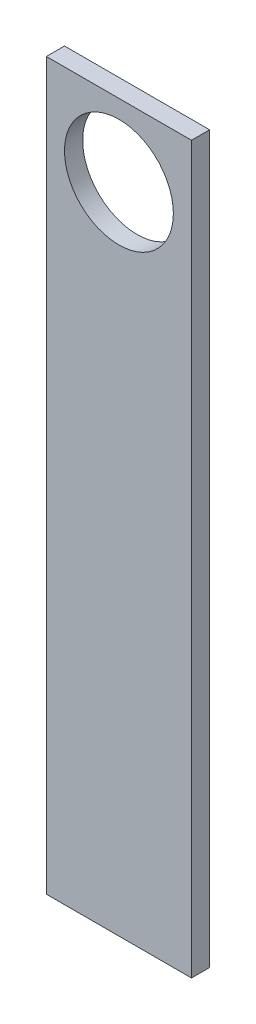
SolidWorks part; units mm, degrees
ref_plane "Front Plane" through (0, 0, 0) normal (0, 0, 1) x (1, 0, 0)
ref_plane "Top Plane" through (0, 0, 0) normal (0, 1, 0) x (1, 0, 0)
ref_plane "Right Plane" through (0, 0, 0) normal (1, 0, 0) x (0, 0, -1)
sketch "Sketch1" plane through (0, 0, 0) normal (0, 0, 1) x (1, 0, 0)
  line L1 (-21.255, 17.0137) -> (4.145, 17.0137)
  line L2 (-21.255, 17.0137) -> (-21.255, -109.9863)
  line L3 (-21.255, -109.9863) -> (4.145, -109.9863)
  line L4 (4.145, 17.0137) -> (4.145, -109.9863)
  dimension "D1" = 25.4
  dimension "D2" = 127
extrude "Boss-Extrude1" add sketch "Sketch1" along normal blind 3.175
sketch "Sketch2" plane through (0, 0, 3.175) normal (0, 0, 1) x (1, 0, 0)
  line L0 (4.145, 17.0137) -> (-21.255, 17.0137) construction
  circle A0 centre (-8.555, 4.3137) radius 9.525
  point P4 (-8.1442, 4.2462)
  point P5 (-8.555, 17.0137)
  point P6 (0, 0)
  dimension "D1" = 19.05
  dimension "D2" = 12.7
extrude "Cut-Extrude1" cut sketch "Sketch2" against normal blind 3.175
